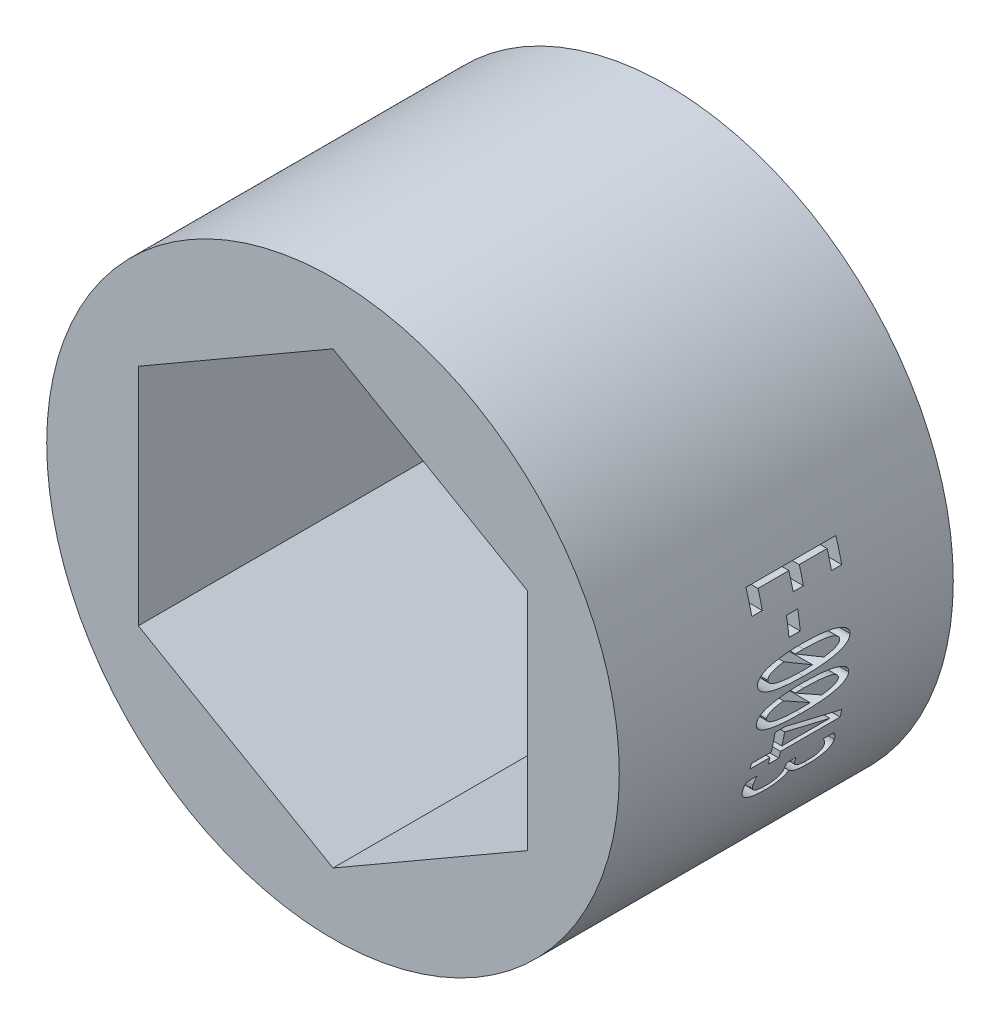
SolidWorks part; units mm, degrees
material "PET"
ref_plane "Front Plane" through (0, 0, 0) normal (0, 0, 1) x (1, 0, 0)
ref_plane "Top Plane" through (0, 0, 0) normal (0, 1, 0) x (1, 0, 0)
ref_plane "Right Plane" through (0, 0, 0) normal (1, 0, 0) x (0, 0, -1)
sketch "Sketch1" plane through (0, 0, 0) normal (0, 0, 1) x (1, 0, 0)
  line L1 (0, 7.479) -> (-6.477, 3.7395)
  line L2 (-6.477, 3.7395) -> (-6.477, -3.7395)
  line L3 (-6.477, -3.7395) -> (0, -7.479)
  line L4 (0, -7.479) -> (6.477, -3.7395)
  line L5 (6.477, -3.7395) -> (6.477, 3.7395)
  line L6 (6.477, 3.7395) -> (0, 7.479)
  circle A0 centre (0, 0) radius 9.525
  circle A1 centre (0, 0) radius 6.477 construction
  dimension "D1" = 12.954
  dimension "D2" = 19.05
extrude "Boss-Extrude1" add sketch "Sketch1" along normal mid plane 11.1125
sketch "Sketch2" plane through (-6.477, 0, 0) normal (1, 0, 0) x (0, 0, -1)
  text T0 "\r\nEE-0043" font "Consolas" height in points 11
extrude "Cut-Extrude4" cut sketch "Sketch2" along normal blind 2.54 from offset 14.2875
